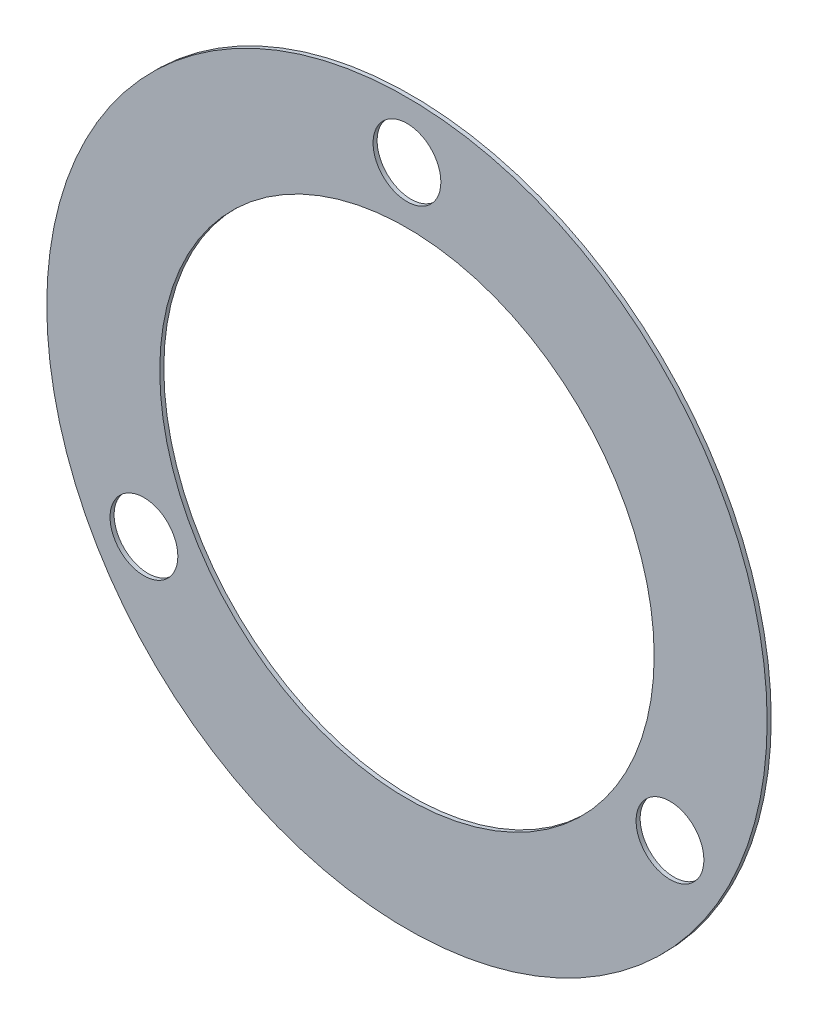
SolidWorks part; units mm, degrees
material "Corrugated Paper"
ref_plane "Front Plane" through (0, 0, 0) normal (0, 0, 1) x (1, 0, 0)
ref_plane "Top Plane" through (0, 0, 0) normal (0, 1, 0) x (1, 0, 0)
ref_plane "Right Plane" through (0, 0, 0) normal (1, 0, 0) x (0, 0, -1)
sketch "Sketch1" plane through (0, 0, 0) normal (0, 0, 1) x (1, 0, 0)
  line L0 (0, 13.8938) -> (0, 20.2438) construction
  line L1 (0, 0) -> (-22.6586, -13.0819) construction
  line L2 (-30.3397, 17.5167) -> (15.8755, -9.1657) construction
  circle A0 centre (0, 0) radius 17.0688 construction
  circle A1 centre (0, 0) radius 20.2438
  circle A2 centre (0, 0) radius 13.8938
  circle A3 centre (0, 17.0688) radius 1.905
  circle A4 centre (14.782, -8.5344) radius 1.905
  circle A5 centre (-14.782, -8.5344) radius 1.905
  point P7 (0, 17.0688)
  dimension "D1" = 34.1376
  dimension "D2" = 6.35
  dimension "D3" = 3.81
  dimension "D4" = 60
  dimension "D5" = 60
extrude "Boss-Extrude1" add sketch "Sketch1" along normal blind 0.2286
